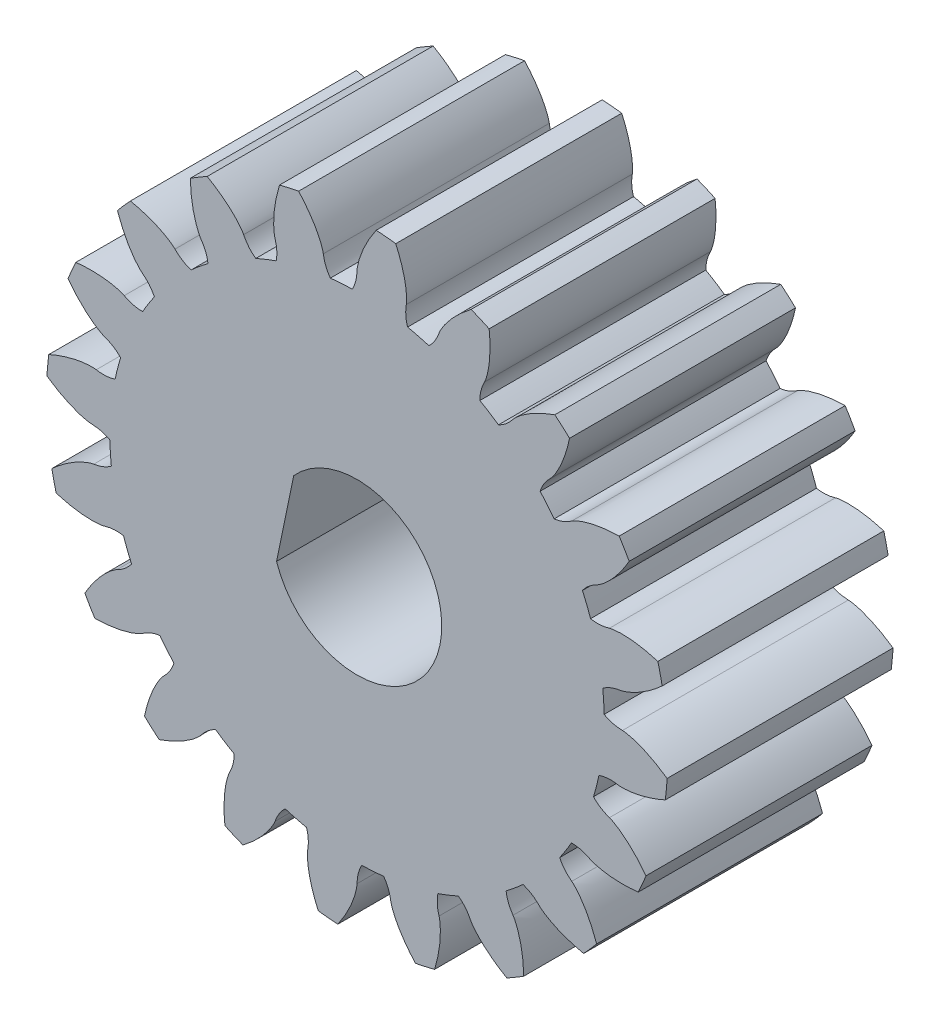
SolidWorks part; units mm, degrees
ref_plane "前视基准面" through (0, 0, 0) normal (0, 0, 1) x (1, 0, 0)
ref_plane "上视基准面" through (0, 0, 0) normal (0, 1, 0) x (1, 0, 0)
ref_plane "右视基准面" through (0, 0, 0) normal (1, 0, 0) x (0, 0, -1)
other "Configuration Table"
sketch "草图2" plane through (0, 0, 0) normal (0, 0, 1) x (1, 0, 0)
  line L0 (0, 0) -> (0.1489, 9.9989) construction
  line L1 (0, 0) -> (1.0263, 10.952) construction
  line L2 (0, 0) -> (2.6039, 10.1758) construction
  circle A0 centre (0, 0) radius 11
  circle A1 centre (0, 0) radius 8.75
  circle A2 centre (0, 0) radius 10
  spline S0 degree 4 poles (0, 9.3969) (0.0002, 9.4045) (0.0012, 9.4259) (0.0051, 9.4662) (0.0144, 9.5316) (0.0306, 9.6143) (0.0564, 9.7204) (0.0929, 9.844) (0.1395, 9.9782) (0.1971, 10.1222) (0.2605, 10.2637) (0.3292, 10.4028) (0.4026, 10.5394) (0.4972, 10.7023) (0.6185, 10.894) (0.7714, 11.1121) (0.9577, 11.3522) (1.1609, 11.5883) (1.3716, 11.8135) (1.5963, 12.032) (1.8221, 12.2371) (2.068, 12.4403) (2.3008, 12.6228) (2.5736, 12.8158) (2.7973, 12.9682) (3.1042, 13.1564) (3.289, 13.2637) (3.5092, 13.3847) (3.609, 13.436) (3.6704, 13.4676) knots 0 0 0 0 0 0.005377 0.015084 0.028532 0.04661 0.064855 0.092111 0.119476 0.146842 0.174209 0.201575 0.228941 0.256307 0.307035 0.361767 0.4165 0.471232 0.525964 0.580697 0.635429 0.690161 0.744894 0.799626 0.854358 0.909091 0.954545 1 1 1 1 1 construction
  spline S1 degree 4 poles (0, 9.3969) (0.0002, 9.4045) (0.0012, 9.4259) (0.0051, 9.4662) (0.0144, 9.5316) (0.0306, 9.6143) (0.0564, 9.7204) (0.0929, 9.844) (0.1395, 9.9782) (0.1971, 10.1222) (0.2605, 10.2637) (0.3292, 10.4028) (0.4026, 10.5394) (0.4971, 10.7022) (0.5769, 10.8283) (0.6386, 10.9201) (0.6797, 10.979) knots 0 0 0 0 0 0.005377 0.015084 0.028532 0.04661 0.064855 0.092111 0.119476 0.146842 0.174209 0.201575 0.228941 0.256307 0.306947 0.306947 0.306947 0.306947 0.306947
  spline S2 degree 3 poles (0, 9.3969) (-0.0051, 9.1654) (-0.0557, 8.9492) (-0.1677, 8.7484) knots 0 0 0 0 1 1 1 1
  spline S3 degree 4 poles (1.7457, 9.2333) (1.747, 9.2409) (1.75, 9.262) (1.7536, 9.3023) (1.7566, 9.3683) (1.7561, 9.4526) (1.7504, 9.5616) (1.7375, 9.6899) (1.7166, 9.8304) (1.6868, 9.9826) (1.6508, 10.1334) (1.6091, 10.2829) (1.5624, 10.4308) (1.4998, 10.6083) (1.4448, 10.747) (1.4012, 10.8486) (1.3718, 10.9141) knots 0 0 0 0 0 0.005377 0.015084 0.028532 0.04661 0.064855 0.092111 0.119476 0.146842 0.174209 0.201575 0.228941 0.256307 0.306947 0.306947 0.306947 0.306947 0.306947
  spline S4 degree 4 poles (2.9038, 8.937) (2.9063, 8.9442) (2.9139, 8.9642) (2.9301, 9.0013) (2.9591, 9.0606) (3.0001, 9.1343) (3.0574, 9.2272) (3.1304, 9.3335) (3.2161, 9.4467) (3.3154, 9.5658) (3.4194, 9.6809) (3.5278, 9.7919) (3.6398, 9.8992) (3.78, 10.0248) (3.8948, 10.12) (3.9819, 10.1883) (4.0391, 10.2316) knots 0 0 0 0 0 0.005377 0.015084 0.028532 0.04661 0.064855 0.092111 0.119476 0.146842 0.174209 0.201575 0.228941 0.256307 0.306947 0.306947 0.306947 0.306947 0.306947
  spline S5 degree 3 poles (1.7457, 9.2333) (1.7077, 9.0049) (1.7173, 8.783) (1.79, 8.5649) knots 0 0 0 0 1 1 1 1
  spline S6 degree 3 poles (2.9038, 8.937) (2.8274, 8.7184) (2.7125, 8.5284) (2.5439, 8.372) knots 0 0 0 0 1 1 1 1
  dimension "D1" = 20
  dimension "D2" = 22
  dimension "D3" = 17.5
  dimension "D5" = 4.5
  dimension "D6" = 13.5
sketch "草图4" plane through (0, 0, 0) normal (0, 0, 1) x (1, 0, 0)
  circle A0 centre (0, 0) radius 8.75 construction
  circle A1 centre (0, 0) radius 11 construction
  arc A2 (2.5439, 8.372) -> (1.79, 8.5649) centre (0, 0) ccw
  arc A3 (1.3718, 10.9141) -> (0.6797, 10.979) centre (0, 0) ccw
  arc A4 (4.6773, 9.956) -> (4.0391, 10.2316) centre (0, 0) ccw
  arc A5 (5.0065, 7.1762) -> (4.3492, 7.5926) centre (0, 0) ccw
  arc A6 (7.525, 8.0234) -> (7.0031, 8.4827) centre (0, 0) ccw
  arc A7 (6.979, 5.2779) -> (6.4825, 5.877) centre (0, 0) ccw
  arc A8 (9.6361, 5.3053) -> (9.2817, 5.9034) centre (0, 0) ccw
  arc A9 (8.2684, 2.8629) -> (7.9813, 3.5862) centre (0, 0) ccw
  arc A10 (10.8039, 2.068) -> (10.6517, 2.7463) centre (0, 0) ccw
  arc A11 (8.7484, 0.1677) -> (8.6989, 0.9443) centre (0, 0) ccw
  arc A12 (10.9141, -1.3718) -> (10.979, -0.6797) centre (0, 0) ccw
  arc A13 (8.372, -2.5439) -> (8.5649, -1.79) centre (0, 0) ccw
  arc A14 (9.956, -4.6773) -> (10.2316, -4.0391) centre (0, 0) ccw
  arc A15 (7.1762, -5.0065) -> (7.5926, -4.3492) centre (0, 0) ccw
  arc A16 (8.0234, -7.525) -> (8.4827, -7.0031) centre (0, 0) ccw
  arc A17 (5.2779, -6.979) -> (5.877, -6.4825) centre (0, 0) ccw
  arc A18 (5.3053, -9.6361) -> (5.9034, -9.2817) centre (0, 0) ccw
  arc A19 (2.8629, -8.2684) -> (3.5862, -7.9813) centre (0, 0) ccw
  arc A20 (2.068, -10.8039) -> (2.7463, -10.6517) centre (0, 0) ccw
  arc A21 (0.1677, -8.7484) -> (0.9443, -8.6989) centre (0, 0) ccw
  arc A22 (-1.3718, -10.9141) -> (-0.6797, -10.979) centre (0, 0) ccw
  arc A23 (-2.5439, -8.372) -> (-1.79, -8.5649) centre (0, 0) ccw
  arc A24 (-4.6773, -9.956) -> (-4.0391, -10.2316) centre (0, 0) ccw
  arc A25 (-5.0065, -7.1762) -> (-4.3492, -7.5926) centre (0, 0) ccw
  arc A26 (-7.525, -8.0234) -> (-7.0031, -8.4827) centre (0, 0) ccw
  arc A27 (-6.979, -5.2779) -> (-6.4825, -5.877) centre (0, 0) ccw
  arc A28 (-9.6361, -5.3053) -> (-9.2817, -5.9034) centre (0, 0) ccw
  arc A29 (-8.2684, -2.8629) -> (-7.9813, -3.5862) centre (0, 0) ccw
  arc A30 (-10.8039, -2.068) -> (-10.6517, -2.7463) centre (0, 0) ccw
  arc A31 (-8.7484, -0.1677) -> (-8.6989, -0.9443) centre (0, 0) ccw
  arc A32 (-10.9141, 1.3718) -> (-10.979, 0.6797) centre (0, 0) ccw
  arc A33 (-8.372, 2.5439) -> (-8.5649, 1.79) centre (0, 0) ccw
  arc A34 (-9.956, 4.6773) -> (-10.2316, 4.0391) centre (0, 0) ccw
  arc A35 (-7.1762, 5.0065) -> (-7.5926, 4.3492) centre (0, 0) ccw
  arc A36 (-8.0234, 7.525) -> (-8.4827, 7.0031) centre (0, 0) ccw
  arc A37 (-5.2779, 6.979) -> (-5.877, 6.4825) centre (0, 0) ccw
  arc A38 (-5.3053, 9.6361) -> (-5.9034, 9.2817) centre (0, 0) ccw
  arc A39 (-2.8629, 8.2684) -> (-3.5862, 7.9813) centre (0, 0) ccw
  arc A40 (-2.068, 10.8039) -> (-2.7463, 10.6517) centre (0, 0) ccw
  arc A41 (-0.1677, 8.7484) -> (-0.9443, 8.6989) centre (0, 0) ccw
  spline S0 degree 3 poles (2.9038, 8.937) (2.8274, 8.7184) (2.7125, 8.5284) (2.5439, 8.372) knots 0 0 0 0 1 1 1 1
  spline S2 degree 3 poles (-1934.3445, 507) (1990.5579, -354.5504) (-1998.9615, 305.4364) (1982.4508, -268.4283) knots -53.013811 -53.013811 -53.013811 -53.013811 47.32506 47.32506 47.32506 47.32506 only from (1.7457, 9.2333) to (1.79, 8.5649) construction
  spline S3 degree 3 poles (1994.8605, 138.8139) (-2021.7734, 21.4251) (2020.9063, -71.2453) (-1997.8078, 104.5418) knots -53.013811 -53.013811 -53.013811 -53.013811 47.32506 47.32506 47.32506 47.32506 only from (0, 9.3969) to (-0.1677, 8.7484) construction
  spline S4 degree 4 poles (-1966.019, 366.2112) (-26.0757, 12.0563) (1.0255, 7.8303) (1.7205, 8.5676) (1.7566, 9.3683) (1.7561, 9.4526) (1.7504, 9.5616) (1.7375, 9.6899) (1.7166, 9.8304) (1.6868, 9.9826) (1.6508, 10.1334) (1.6091, 10.2829) (1.5624, 10.4308) (0.1488, 14.4374) (-5.4103, 16.6364) (-16.4638, 28.6234) (1468.9037, -1347.863) knots -0.51893 -0.51893 -0.51893 -0.51893 -0.51893 0.005377 0.015084 0.028532 0.04661 0.064855 0.092111 0.119476 0.146842 0.174209 0.201575 0.228941 0.256307 3.170222 3.170222 3.170222 3.170222 3.170222 only from (1.7457, 9.2333) to (1.3718, 10.9141) construction
  spline S5 degree 4 poles (1999.828, -5.4085) (27.8615, 7.0021) (0.4471, 7.8845) (-0.0989, 8.7381) (0.0144, 9.5316) (0.0306, 9.6143) (0.0564, 9.7204) (0.0929, 9.844) (0.1395, 9.9782) (0.1971, 10.1222) (0.2605, 10.2637) (0.3292, 10.4028) (0.4026, 10.5394) (2.536, 14.2137) (8.4068, 15.3416) (21.4948, 25.0665) (-1693.7368, -1051.5077) knots -0.51893 -0.51893 -0.51893 -0.51893 -0.51893 0.005377 0.015084 0.028532 0.04661 0.064855 0.092111 0.119476 0.146842 0.174209 0.201575 0.228941 0.256307 3.170222 3.170222 3.170222 3.170222 3.170222 only from (0, 9.3969) to (0.6797, 10.979) construction
  spline S6 degree 4 poles (2.9038, 8.937) (2.9063, 8.9442) (2.9139, 8.9642) (2.9301, 9.0013) (2.9591, 9.0606) (3.0001, 9.1343) (3.0574, 9.2272) (3.1304, 9.3335) (3.2161, 9.4467) (3.3154, 9.5658) (3.4194, 9.6809) (3.5278, 9.7919) (3.6398, 9.8992) (3.78, 10.0248) (3.8948, 10.12) (3.9819, 10.1883) (4.0391, 10.2316) knots 0 0 0 0 0 0.005377 0.015084 0.028532 0.04661 0.064855 0.092111 0.119476 0.146842 0.174209 0.201575 0.228941 0.256307 0.306947 0.306947 0.306947 0.306947 0.306947
  spline S7 degree 4 poles (4.5136, 8.242) (4.5171, 8.2487) (4.5265, 8.2679) (4.5423, 8.3051) (4.5656, 8.367) (4.5911, 8.4473) (4.6195, 8.5527) (4.6468, 8.6787) (4.6704, 8.8188) (4.689, 8.9727) (4.7014, 9.1273) (4.708, 9.2824) (4.7092, 9.4374) (4.7045, 9.6256) (4.6951, 9.7745) (4.685, 9.8847) (4.6773, 9.956) knots 0 0 0 0 0 0.005377 0.015084 0.028532 0.04661 0.064855 0.092111 0.119476 0.146842 0.174209 0.201575 0.228941 0.256307 0.306947 0.306947 0.306947 0.306947 0.306947
  spline S8 degree 3 poles (1.7457, 9.2333) (1.7077, 9.0049) (1.7173, 8.783) (1.79, 8.5649) knots 0 0 0 0 1 1 1 1
  spline S9 degree 3 poles (0, 9.3969) (-0.0051, 9.1654) (-0.0557, 8.9492) (-0.1677, 8.7484) knots 0 0 0 0 1 1 1 1
  spline S10 degree 4 poles (1.7457, 9.2333) (1.747, 9.2409) (1.75, 9.262) (1.7536, 9.3023) (1.7566, 9.3683) (1.7561, 9.4526) (1.7504, 9.5616) (1.7375, 9.6899) (1.7166, 9.8304) (1.6868, 9.9826) (1.6508, 10.1334) (1.6091, 10.2829) (1.5624, 10.4308) (1.4998, 10.6083) (1.4448, 10.747) (1.4012, 10.8486) (1.3718, 10.9141) knots 0 0 0 0 0 0.005377 0.015084 0.028532 0.04661 0.064855 0.092111 0.119476 0.146842 0.174209 0.201575 0.228941 0.256307 0.306947 0.306947 0.306947 0.306947 0.306947
  spline S11 degree 4 poles (0, 9.3969) (0.0002, 9.4045) (0.0012, 9.4259) (0.0051, 9.4662) (0.0144, 9.5316) (0.0306, 9.6143) (0.0564, 9.7204) (0.0929, 9.844) (0.1395, 9.9782) (0.1971, 10.1222) (0.2605, 10.2637) (0.3292, 10.4028) (0.4026, 10.5394) (0.4971, 10.7022) (0.5769, 10.8283) (0.6386, 10.9201) (0.6797, 10.979) knots 0 0 0 0 0 0.005377 0.015084 0.028532 0.04661 0.064855 0.092111 0.119476 0.146842 0.174209 0.201575 0.228941 0.256307 0.306947 0.306947 0.306947 0.306947 0.306947
  spline S12 degree 3 poles (4.5136, 8.242) (4.4068, 8.0365) (4.3473, 7.8225) (4.3492, 7.5926) knots 0 0 0 0 1 1 1 1
  spline S13 degree 3 poles (5.5234, 7.6023) (5.3832, 7.418) (5.2151, 7.2727) (5.0065, 7.1762) knots 0 0 0 0 1 1 1 1
  spline S14 degree 4 poles (5.5234, 7.6023) (5.528, 7.6083) (5.5413, 7.625) (5.5682, 7.6553) (5.6142, 7.7027) (5.6759, 7.7601) (5.7591, 7.8308) (5.8614, 7.9094) (5.9779, 7.9905) (6.1091, 8.0731) (6.2436, 8.1504) (6.381, 8.2226) (6.5207, 8.2899) (6.6928, 8.3661) (6.8314, 8.4212) (6.9353, 8.4592) (7.0031, 8.4827) knots 0 0 0 0 0 0.005377 0.015084 0.028532 0.04661 0.064855 0.092111 0.119476 0.146842 0.174209 0.201575 0.228941 0.256307 0.306947 0.306947 0.306947 0.306947 0.306947
  spline S15 degree 4 poles (6.8396, 6.4438) (6.845, 6.4492) (6.8599, 6.4645) (6.8865, 6.495) (6.9276, 6.5466) (6.9768, 6.6151) (7.0363, 6.7066) (7.1013, 6.818) (7.167, 6.944) (7.2323, 7.0846) (7.2918, 7.2278) (7.3459, 7.3732) (7.395, 7.5203) (7.4487, 7.7007) (7.4858, 7.8452) (7.5103, 7.9531) (7.525, 8.0234) knots 0 0 0 0 0 0.005377 0.015084 0.028532 0.04661 0.064855 0.092111 0.119476 0.146842 0.174209 0.201575 0.228941 0.256307 0.306947 0.306947 0.306947 0.306947 0.306947
  spline S16 degree 3 poles (6.8396, 6.4438) (6.6746, 6.2813) (6.5518, 6.0962) (6.4825, 5.877) knots 0 0 0 0 1 1 1 1
  spline S17 degree 3 poles (7.6023, 5.5234) (7.412, 5.3914) (7.2073, 5.3052) (6.979, 5.2779) knots 0 0 0 0 1 1 1 1
  spline S18 degree 4 poles (7.6023, 5.5234) (7.6085, 5.5277) (7.6264, 5.5395) (7.6613, 5.5599) (7.7197, 5.5908) (7.7961, 5.6264) (7.8971, 5.6679) (8.0186, 5.711) (8.1546, 5.7522) (8.3048, 5.7902) (8.4566, 5.8221) (8.6096, 5.8483) (8.7632, 5.8692) (8.9505, 5.8884) (9.0994, 5.898) (9.2099, 5.902) (9.2817, 5.9034) knots 0 0 0 0 0 0.005377 0.015084 0.028532 0.04661 0.064855 0.092111 0.119476 0.146842 0.174209 0.201575 0.228941 0.256307 0.306947 0.306947 0.306947 0.306947 0.306947
  spline S19 degree 4 poles (8.4961, 4.0149) (8.5029, 4.0183) (8.5218, 4.0283) (8.5565, 4.0491) (8.6116, 4.0855) (8.6795, 4.1354) (8.7644, 4.2041) (8.8606, 4.2899) (8.962, 4.3894) (9.0676, 4.5029) (9.1684, 4.6207) (9.2649, 4.7423) (9.357, 4.8671) (9.4638, 5.0221) (9.5437, 5.148) (9.6003, 5.2431) (9.6361, 5.3053) knots 0 0 0 0 0 0.005377 0.015084 0.028532 0.04661 0.064855 0.092111 0.119476 0.146842 0.174209 0.201575 0.228941 0.256307 0.306947 0.306947 0.306947 0.306947 0.306947
  spline S20 degree 3 poles (8.4961, 4.0149) (8.2889, 3.9114) (8.115, 3.7732) (7.9813, 3.5862) knots 0 0 0 0 1 1 1 1
  spline S21 degree 3 poles (8.937, 2.9038) (8.7153, 2.8371) (8.494, 2.8184) (8.2684, 2.8629) knots 0 0 0 0 1 1 1 1
  spline S22 degree 4 poles (8.937, 2.9038) (8.9443, 2.906) (8.9649, 2.9117) (9.0044, 2.9204) (9.0695, 2.9317) (9.1532, 2.9419) (9.2621, 2.9502) (9.3909, 2.9536) (9.533, 2.9507) (9.6876, 2.9405) (9.8419, 2.9239) (9.9954, 2.9015) (10.148, 2.8739) (10.332, 2.8344) (10.4766, 2.7974) (10.583, 2.7671) (10.6517, 2.7463) knots 0 0 0 0 0 0.005377 0.015084 0.028532 0.04661 0.064855 0.092111 0.119476 0.146842 0.174209 0.201575 0.228941 0.256307 0.306947 0.306947 0.306947 0.306947 0.306947
  spline S23 degree 4 poles (9.3209, 1.193) (9.3284, 1.1941) (9.3495, 1.1978) (9.3889, 1.2068) (9.4526, 1.2244) (9.5326, 1.2509) (9.6346, 1.2899) (9.7526, 1.3419) (9.8798, 1.4052) (10.0152, 1.4805) (10.1476, 1.5614) (10.2769, 1.6472) (10.403, 1.7374) (10.5525, 1.8518) (10.6674, 1.9469) (10.7507, 2.0198) (10.8039, 2.068) knots 0 0 0 0 0 0.005377 0.015084 0.028532 0.04661 0.064855 0.092111 0.119476 0.146842 0.174209 0.201575 0.228941 0.256307 0.306947 0.306947 0.306947 0.306947 0.306947
  spline S24 degree 3 poles (9.3209, 1.193) (9.0919, 1.1585) (8.8838, 1.0809) (8.6989, 0.9443) knots 0 0 0 0 1 1 1 1
  spline S25 degree 3 poles (9.3969, 0) (9.1654, 0.0051) (8.9492, 0.0557) (8.7484, 0.1677) knots 0 0 0 0 1 1 1 1
  spline S26 degree 4 poles (9.3969, 0) (9.4045, -0.0002) (9.4259, -0.0012) (9.4662, -0.0051) (9.5316, -0.0144) (9.6143, -0.0306) (9.7204, -0.0564) (9.844, -0.0929) (9.9782, -0.1395) (10.1222, -0.1971) (10.2637, -0.2605) (10.4028, -0.3292) (10.5394, -0.4026) (10.7022, -0.4971) (10.8283, -0.5769) (10.9201, -0.6386) (10.979, -0.6797) knots 0 0 0 0 0 0.005377 0.015084 0.028532 0.04661 0.064855 0.092111 0.119476 0.146842 0.174209 0.201575 0.228941 0.256307 0.306947 0.306947 0.306947 0.306947 0.306947
  spline S27 degree 4 poles (9.2333, -1.7457) (9.2409, -1.747) (9.262, -1.75) (9.3023, -1.7536) (9.3683, -1.7566) (9.4526, -1.7561) (9.5616, -1.7504) (9.6899, -1.7375) (9.8304, -1.7166) (9.9826, -1.6868) (10.1334, -1.6508) (10.2829, -1.6091) (10.4308, -1.5624) (10.6083, -1.4998) (10.747, -1.4448) (10.8486, -1.4012) (10.9141, -1.3718) knots 0 0 0 0 0 0.005377 0.015084 0.028532 0.04661 0.064855 0.092111 0.119476 0.146842 0.174209 0.201575 0.228941 0.256307 0.306947 0.306947 0.306947 0.306947 0.306947
  spline S28 degree 3 poles (9.2333, -1.7457) (9.0049, -1.7077) (8.783, -1.7173) (8.5649, -1.79) knots 0 0 0 0 1 1 1 1
  spline S29 degree 3 poles (8.937, -2.9038) (8.7184, -2.8274) (8.5284, -2.7125) (8.372, -2.5439) knots 0 0 0 0 1 1 1 1
  spline S30 degree 4 poles (8.937, -2.9038) (8.9442, -2.9063) (8.9642, -2.9139) (9.0013, -2.9301) (9.0606, -2.9591) (9.1343, -3.0001) (9.2272, -3.0574) (9.3335, -3.1304) (9.4467, -3.2161) (9.5658, -3.3154) (9.6809, -3.4194) (9.7919, -3.5278) (9.8992, -3.6398) (10.0248, -3.78) (10.12, -3.8948) (10.1883, -3.9819) (10.2316, -4.0391) knots 0 0 0 0 0 0.005377 0.015084 0.028532 0.04661 0.064855 0.092111 0.119476 0.146842 0.174209 0.201575 0.228941 0.256307 0.306947 0.306947 0.306947 0.306947 0.306947
  spline S31 degree 4 poles (8.242, -4.5136) (8.2487, -4.5171) (8.2679, -4.5265) (8.3051, -4.5423) (8.367, -4.5656) (8.4473, -4.5911) (8.5527, -4.6195) (8.6787, -4.6468) (8.8188, -4.6704) (8.9727, -4.689) (9.1273, -4.7014) (9.2824, -4.708) (9.4374, -4.7092) (9.6256, -4.7045) (9.7745, -4.6951) (9.8847, -4.685) (9.956, -4.6773) knots 0 0 0 0 0 0.005377 0.015084 0.028532 0.04661 0.064855 0.092111 0.119476 0.146842 0.174209 0.201575 0.228941 0.256307 0.306947 0.306947 0.306947 0.306947 0.306947
  spline S32 degree 3 poles (8.242, -4.5136) (8.0365, -4.4068) (7.8225, -4.3473) (7.5926, -4.3492) knots 0 0 0 0 1 1 1 1
  spline S33 degree 3 poles (7.6023, -5.5234) (7.418, -5.3832) (7.2727, -5.2151) (7.1762, -5.0065) knots 0 0 0 0 1 1 1 1
  spline S34 degree 4 poles (7.6023, -5.5234) (7.6083, -5.528) (7.625, -5.5413) (7.6553, -5.5682) (7.7027, -5.6142) (7.7601, -5.6759) (7.8308, -5.7591) (7.9094, -5.8614) (7.9905, -5.9779) (8.0731, -6.1091) (8.1504, -6.2436) (8.2226, -6.381) (8.2899, -6.5207) (8.3661, -6.6928) (8.4212, -6.8314) (8.4592, -6.9353) (8.4827, -7.0031) knots 0 0 0 0 0 0.005377 0.015084 0.028532 0.04661 0.064855 0.092111 0.119476 0.146842 0.174209 0.201575 0.228941 0.256307 0.306947 0.306947 0.306947 0.306947 0.306947
  spline S35 degree 4 poles (6.4438, -6.8396) (6.4492, -6.845) (6.4645, -6.8599) (6.495, -6.8865) (6.5466, -6.9276) (6.6151, -6.9768) (6.7066, -7.0363) (6.818, -7.1013) (6.944, -7.167) (7.0846, -7.2323) (7.2278, -7.2918) (7.3732, -7.3459) (7.5203, -7.395) (7.7007, -7.4487) (7.8452, -7.4858) (7.9531, -7.5103) (8.0234, -7.525) knots 0 0 0 0 0 0.005377 0.015084 0.028532 0.04661 0.064855 0.092111 0.119476 0.146842 0.174209 0.201575 0.228941 0.256307 0.306947 0.306947 0.306947 0.306947 0.306947
  spline S36 degree 3 poles (6.4438, -6.8396) (6.2813, -6.6746) (6.0962, -6.5518) (5.877, -6.4825) knots 0 0 0 0 1 1 1 1
  spline S37 degree 3 poles (5.5234, -7.6023) (5.3914, -7.412) (5.3052, -7.2073) (5.2779, -6.979) knots 0 0 0 0 1 1 1 1
  spline S38 degree 4 poles (5.5234, -7.6023) (5.5277, -7.6085) (5.5395, -7.6264) (5.5599, -7.6613) (5.5908, -7.7197) (5.6264, -7.7961) (5.6679, -7.8971) (5.711, -8.0186) (5.7522, -8.1546) (5.7902, -8.3048) (5.8221, -8.4566) (5.8483, -8.6096) (5.8692, -8.7632) (5.8884, -8.9505) (5.898, -9.0994) (5.902, -9.2099) (5.9034, -9.2817) knots 0 0 0 0 0 0.005377 0.015084 0.028532 0.04661 0.064855 0.092111 0.119476 0.146842 0.174209 0.201575 0.228941 0.256307 0.306947 0.306947 0.306947 0.306947 0.306947
  spline S39 degree 4 poles (4.0149, -8.4961) (4.0183, -8.5029) (4.0283, -8.5218) (4.0491, -8.5565) (4.0855, -8.6116) (4.1354, -8.6795) (4.2041, -8.7644) (4.2899, -8.8606) (4.3894, -8.962) (4.5029, -9.0676) (4.6207, -9.1684) (4.7423, -9.2649) (4.8671, -9.357) (5.0221, -9.4638) (5.148, -9.5437) (5.2431, -9.6003) (5.3053, -9.6361) knots 0 0 0 0 0 0.005377 0.015084 0.028532 0.04661 0.064855 0.092111 0.119476 0.146842 0.174209 0.201575 0.228941 0.256307 0.306947 0.306947 0.306947 0.306947 0.306947
  spline S40 degree 3 poles (4.0149, -8.4961) (3.9114, -8.2889) (3.7732, -8.115) (3.5862, -7.9813) knots 0 0 0 0 1 1 1 1
  spline S41 degree 3 poles (2.9038, -8.937) (2.8371, -8.7153) (2.8184, -8.494) (2.8629, -8.2684) knots 0 0 0 0 1 1 1 1
  spline S42 degree 4 poles (2.9038, -8.937) (2.906, -8.9443) (2.9117, -8.9649) (2.9204, -9.0044) (2.9317, -9.0695) (2.9419, -9.1532) (2.9502, -9.2621) (2.9536, -9.3909) (2.9507, -9.533) (2.9405, -9.6876) (2.9239, -9.8419) (2.9015, -9.9954) (2.8739, -10.148) (2.8344, -10.332) (2.7974, -10.4766) (2.7671, -10.583) (2.7463, -10.6517) knots 0 0 0 0 0 0.005377 0.015084 0.028532 0.04661 0.064855 0.092111 0.119476 0.146842 0.174209 0.201575 0.228941 0.256307 0.306947 0.306947 0.306947 0.306947 0.306947
  spline S43 degree 4 poles (1.193, -9.3209) (1.1941, -9.3284) (1.1978, -9.3495) (1.2068, -9.3889) (1.2244, -9.4526) (1.2509, -9.5326) (1.2899, -9.6346) (1.3419, -9.7526) (1.4052, -9.8798) (1.4805, -10.0152) (1.5614, -10.1476) (1.6472, -10.2769) (1.7374, -10.403) (1.8518, -10.5525) (1.9469, -10.6674) (2.0198, -10.7507) (2.068, -10.8039) knots 0 0 0 0 0 0.005377 0.015084 0.028532 0.04661 0.064855 0.092111 0.119476 0.146842 0.174209 0.201575 0.228941 0.256307 0.306947 0.306947 0.306947 0.306947 0.306947
  spline S44 degree 3 poles (1.193, -9.3209) (1.1585, -9.0919) (1.0809, -8.8838) (0.9443, -8.6989) knots 0 0 0 0 1 1 1 1
  spline S45 degree 3 poles (0, -9.3969) (0.0051, -9.1654) (0.0557, -8.9492) (0.1677, -8.7484) knots 0 0 0 0 1 1 1 1
  spline S46 degree 4 poles (0, -9.3969) (-0.0002, -9.4045) (-0.0012, -9.4259) (-0.0051, -9.4662) (-0.0144, -9.5316) (-0.0306, -9.6143) (-0.0564, -9.7204) (-0.0929, -9.844) (-0.1395, -9.9782) (-0.1971, -10.1222) (-0.2605, -10.2637) (-0.3292, -10.4028) (-0.4026, -10.5394) (-0.4971, -10.7022) (-0.5769, -10.8283) (-0.6386, -10.9201) (-0.6797, -10.979) knots 0 0 0 0 0 0.005377 0.015084 0.028532 0.04661 0.064855 0.092111 0.119476 0.146842 0.174209 0.201575 0.228941 0.256307 0.306947 0.306947 0.306947 0.306947 0.306947
  spline S47 degree 4 poles (-1.7457, -9.2333) (-1.747, -9.2409) (-1.75, -9.262) (-1.7536, -9.3023) (-1.7566, -9.3683) (-1.7561, -9.4526) (-1.7504, -9.5616) (-1.7375, -9.6899) (-1.7166, -9.8304) (-1.6868, -9.9826) (-1.6508, -10.1334) (-1.6091, -10.2829) (-1.5624, -10.4308) (-1.4998, -10.6083) (-1.4448, -10.747) (-1.4012, -10.8486) (-1.3718, -10.9141) knots 0 0 0 0 0 0.005377 0.015084 0.028532 0.04661 0.064855 0.092111 0.119476 0.146842 0.174209 0.201575 0.228941 0.256307 0.306947 0.306947 0.306947 0.306947 0.306947
  spline S48 degree 3 poles (-1.7457, -9.2333) (-1.7077, -9.0049) (-1.7173, -8.783) (-1.79, -8.5649) knots 0 0 0 0 1 1 1 1
  spline S49 degree 3 poles (-2.9038, -8.937) (-2.8274, -8.7184) (-2.7125, -8.5284) (-2.5439, -8.372) knots 0 0 0 0 1 1 1 1
  spline S50 degree 4 poles (-2.9038, -8.937) (-2.9063, -8.9442) (-2.9139, -8.9642) (-2.9301, -9.0013) (-2.9591, -9.0606) (-3.0001, -9.1343) (-3.0574, -9.2272) (-3.1304, -9.3335) (-3.2161, -9.4467) (-3.3154, -9.5658) (-3.4194, -9.6809) (-3.5278, -9.7919) (-3.6398, -9.8992) (-3.78, -10.0248) (-3.8948, -10.12) (-3.9819, -10.1883) (-4.0391, -10.2316) knots 0 0 0 0 0 0.005377 0.015084 0.028532 0.04661 0.064855 0.092111 0.119476 0.146842 0.174209 0.201575 0.228941 0.256307 0.306947 0.306947 0.306947 0.306947 0.306947
  spline S51 degree 4 poles (-4.5136, -8.242) (-4.5171, -8.2487) (-4.5265, -8.2679) (-4.5423, -8.3051) (-4.5656, -8.367) (-4.5911, -8.4473) (-4.6195, -8.5527) (-4.6468, -8.6787) (-4.6704, -8.8188) (-4.689, -8.9727) (-4.7014, -9.1273) (-4.708, -9.2824) (-4.7092, -9.4374) (-4.7045, -9.6256) (-4.6951, -9.7745) (-4.685, -9.8847) (-4.6773, -9.956) knots 0 0 0 0 0 0.005377 0.015084 0.028532 0.04661 0.064855 0.092111 0.119476 0.146842 0.174209 0.201575 0.228941 0.256307 0.306947 0.306947 0.306947 0.306947 0.306947
  spline S52 degree 3 poles (-4.5136, -8.242) (-4.4068, -8.0365) (-4.3473, -7.8225) (-4.3492, -7.5926) knots 0 0 0 0 1 1 1 1
  spline S53 degree 3 poles (-5.5234, -7.6023) (-5.3832, -7.418) (-5.2151, -7.2727) (-5.0065, -7.1762) knots 0 0 0 0 1 1 1 1
  spline S54 degree 4 poles (-5.5234, -7.6023) (-5.528, -7.6083) (-5.5413, -7.625) (-5.5682, -7.6553) (-5.6142, -7.7027) (-5.6759, -7.7601) (-5.7591, -7.8308) (-5.8614, -7.9094) (-5.9779, -7.9905) (-6.1091, -8.0731) (-6.2436, -8.1504) (-6.381, -8.2226) (-6.5207, -8.2899) (-6.6928, -8.3661) (-6.8314, -8.4212) (-6.9353, -8.4592) (-7.0031, -8.4827) knots 0 0 0 0 0 0.005377 0.015084 0.028532 0.04661 0.064855 0.092111 0.119476 0.146842 0.174209 0.201575 0.228941 0.256307 0.306947 0.306947 0.306947 0.306947 0.306947
  spline S55 degree 4 poles (-6.8396, -6.4438) (-6.845, -6.4492) (-6.8599, -6.4645) (-6.8865, -6.495) (-6.9276, -6.5466) (-6.9768, -6.6151) (-7.0363, -6.7066) (-7.1013, -6.818) (-7.167, -6.944) (-7.2323, -7.0846) (-7.2918, -7.2278) (-7.3459, -7.3732) (-7.395, -7.5203) (-7.4487, -7.7007) (-7.4858, -7.8452) (-7.5103, -7.9531) (-7.525, -8.0234) knots 0 0 0 0 0 0.005377 0.015084 0.028532 0.04661 0.064855 0.092111 0.119476 0.146842 0.174209 0.201575 0.228941 0.256307 0.306947 0.306947 0.306947 0.306947 0.306947
  spline S56 degree 3 poles (-6.8396, -6.4438) (-6.6746, -6.2813) (-6.5518, -6.0962) (-6.4825, -5.877) knots 0 0 0 0 1 1 1 1
  spline S57 degree 3 poles (-7.6023, -5.5234) (-7.412, -5.3914) (-7.2073, -5.3052) (-6.979, -5.2779) knots 0 0 0 0 1 1 1 1
  spline S58 degree 4 poles (-7.6023, -5.5234) (-7.6085, -5.5277) (-7.6264, -5.5395) (-7.6613, -5.5599) (-7.7197, -5.5908) (-7.7961, -5.6264) (-7.8971, -5.6679) (-8.0186, -5.711) (-8.1546, -5.7522) (-8.3048, -5.7902) (-8.4566, -5.8221) (-8.6096, -5.8483) (-8.7632, -5.8692) (-8.9505, -5.8884) (-9.0994, -5.898) (-9.2099, -5.902) (-9.2817, -5.9034) knots 0 0 0 0 0 0.005377 0.015084 0.028532 0.04661 0.064855 0.092111 0.119476 0.146842 0.174209 0.201575 0.228941 0.256307 0.306947 0.306947 0.306947 0.306947 0.306947
  spline S59 degree 4 poles (-8.4961, -4.0149) (-8.5029, -4.0183) (-8.5218, -4.0283) (-8.5565, -4.0491) (-8.6116, -4.0855) (-8.6795, -4.1354) (-8.7644, -4.2041) (-8.8606, -4.2899) (-8.962, -4.3894) (-9.0676, -4.5029) (-9.1684, -4.6207) (-9.2649, -4.7423) (-9.357, -4.8671) (-9.4638, -5.0221) (-9.5437, -5.148) (-9.6003, -5.2431) (-9.6361, -5.3053) knots 0 0 0 0 0 0.005377 0.015084 0.028532 0.04661 0.064855 0.092111 0.119476 0.146842 0.174209 0.201575 0.228941 0.256307 0.306947 0.306947 0.306947 0.306947 0.306947
  spline S60 degree 3 poles (-8.4961, -4.0149) (-8.2889, -3.9114) (-8.115, -3.7732) (-7.9813, -3.5862) knots 0 0 0 0 1 1 1 1
  spline S61 degree 3 poles (-8.937, -2.9038) (-8.7153, -2.8371) (-8.494, -2.8184) (-8.2684, -2.8629) knots 0 0 0 0 1 1 1 1
  spline S62 degree 4 poles (-8.937, -2.9038) (-8.9443, -2.906) (-8.9649, -2.9117) (-9.0044, -2.9204) (-9.0695, -2.9317) (-9.1532, -2.9419) (-9.2621, -2.9502) (-9.3909, -2.9536) (-9.533, -2.9507) (-9.6876, -2.9405) (-9.8419, -2.9239) (-9.9954, -2.9015) (-10.148, -2.8739) (-10.332, -2.8344) (-10.4766, -2.7974) (-10.583, -2.7671) (-10.6517, -2.7463) knots 0 0 0 0 0 0.005377 0.015084 0.028532 0.04661 0.064855 0.092111 0.119476 0.146842 0.174209 0.201575 0.228941 0.256307 0.306947 0.306947 0.306947 0.306947 0.306947
  spline S63 degree 4 poles (-9.3209, -1.193) (-9.3284, -1.1941) (-9.3495, -1.1978) (-9.3889, -1.2068) (-9.4526, -1.2244) (-9.5326, -1.2509) (-9.6346, -1.2899) (-9.7526, -1.3419) (-9.8798, -1.4052) (-10.0152, -1.4805) (-10.1476, -1.5614) (-10.2769, -1.6472) (-10.403, -1.7374) (-10.5525, -1.8518) (-10.6674, -1.9469) (-10.7507, -2.0198) (-10.8039, -2.068) knots 0 0 0 0 0 0.005377 0.015084 0.028532 0.04661 0.064855 0.092111 0.119476 0.146842 0.174209 0.201575 0.228941 0.256307 0.306947 0.306947 0.306947 0.306947 0.306947
  spline S64 degree 3 poles (-9.3209, -1.193) (-9.0919, -1.1585) (-8.8838, -1.0809) (-8.6989, -0.9443) knots 0 0 0 0 1 1 1 1
  spline S65 degree 3 poles (-9.3969, 0) (-9.1654, -0.0051) (-8.9492, -0.0557) (-8.7484, -0.1677) knots 0 0 0 0 1 1 1 1
  spline S66 degree 4 poles (-9.3969, 0) (-9.4045, 0.0002) (-9.4259, 0.0012) (-9.4662, 0.0051) (-9.5316, 0.0144) (-9.6143, 0.0306) (-9.7204, 0.0564) (-9.844, 0.0929) (-9.9782, 0.1395) (-10.1222, 0.1971) (-10.2637, 0.2605) (-10.4028, 0.3292) (-10.5394, 0.4026) (-10.7022, 0.4971) (-10.8283, 0.5769) (-10.9201, 0.6386) (-10.979, 0.6797) knots 0 0 0 0 0 0.005377 0.015084 0.028532 0.04661 0.064855 0.092111 0.119476 0.146842 0.174209 0.201575 0.228941 0.256307 0.306947 0.306947 0.306947 0.306947 0.306947
  spline S67 degree 4 poles (-9.2333, 1.7457) (-9.2409, 1.747) (-9.262, 1.75) (-9.3023, 1.7536) (-9.3683, 1.7566) (-9.4526, 1.7561) (-9.5616, 1.7504) (-9.6899, 1.7375) (-9.8304, 1.7166) (-9.9826, 1.6868) (-10.1334, 1.6508) (-10.2829, 1.6091) (-10.4308, 1.5624) (-10.6083, 1.4998) (-10.747, 1.4448) (-10.8486, 1.4012) (-10.9141, 1.3718) knots 0 0 0 0 0 0.005377 0.015084 0.028532 0.04661 0.064855 0.092111 0.119476 0.146842 0.174209 0.201575 0.228941 0.256307 0.306947 0.306947 0.306947 0.306947 0.306947
  spline S68 degree 3 poles (-9.2333, 1.7457) (-9.0049, 1.7077) (-8.783, 1.7173) (-8.5649, 1.79) knots 0 0 0 0 1 1 1 1
  spline S69 degree 3 poles (-8.937, 2.9038) (-8.7184, 2.8274) (-8.5284, 2.7125) (-8.372, 2.5439) knots 0 0 0 0 1 1 1 1
  spline S70 degree 4 poles (-8.937, 2.9038) (-8.9442, 2.9063) (-8.9642, 2.9139) (-9.0013, 2.9301) (-9.0606, 2.9591) (-9.1343, 3.0001) (-9.2272, 3.0574) (-9.3335, 3.1304) (-9.4467, 3.2161) (-9.5658, 3.3154) (-9.6809, 3.4194) (-9.7919, 3.5278) (-9.8992, 3.6398) (-10.0248, 3.78) (-10.12, 3.8948) (-10.1883, 3.9819) (-10.2316, 4.0391) knots 0 0 0 0 0 0.005377 0.015084 0.028532 0.04661 0.064855 0.092111 0.119476 0.146842 0.174209 0.201575 0.228941 0.256307 0.306947 0.306947 0.306947 0.306947 0.306947
  spline S71 degree 4 poles (-8.242, 4.5136) (-8.2487, 4.5171) (-8.2679, 4.5265) (-8.3051, 4.5423) (-8.367, 4.5656) (-8.4473, 4.5911) (-8.5527, 4.6195) (-8.6787, 4.6468) (-8.8188, 4.6704) (-8.9727, 4.689) (-9.1273, 4.7014) (-9.2824, 4.708) (-9.4374, 4.7092) (-9.6256, 4.7045) (-9.7745, 4.6951) (-9.8847, 4.685) (-9.956, 4.6773) knots 0 0 0 0 0 0.005377 0.015084 0.028532 0.04661 0.064855 0.092111 0.119476 0.146842 0.174209 0.201575 0.228941 0.256307 0.306947 0.306947 0.306947 0.306947 0.306947
  spline S72 degree 3 poles (-8.242, 4.5136) (-8.0365, 4.4068) (-7.8225, 4.3473) (-7.5926, 4.3492) knots 0 0 0 0 1 1 1 1
  spline S73 degree 3 poles (-7.6023, 5.5234) (-7.418, 5.3832) (-7.2727, 5.2151) (-7.1762, 5.0065) knots 0 0 0 0 1 1 1 1
  spline S74 degree 4 poles (-7.6023, 5.5234) (-7.6083, 5.528) (-7.625, 5.5413) (-7.6553, 5.5682) (-7.7027, 5.6142) (-7.7601, 5.6759) (-7.8308, 5.7591) (-7.9094, 5.8614) (-7.9905, 5.9779) (-8.0731, 6.1091) (-8.1504, 6.2436) (-8.2226, 6.381) (-8.2899, 6.5207) (-8.3661, 6.6928) (-8.4212, 6.8314) (-8.4592, 6.9353) (-8.4827, 7.0031) knots 0 0 0 0 0 0.005377 0.015084 0.028532 0.04661 0.064855 0.092111 0.119476 0.146842 0.174209 0.201575 0.228941 0.256307 0.306947 0.306947 0.306947 0.306947 0.306947
  spline S75 degree 4 poles (-6.4438, 6.8396) (-6.4492, 6.845) (-6.4645, 6.8599) (-6.495, 6.8865) (-6.5466, 6.9276) (-6.6151, 6.9768) (-6.7066, 7.0363) (-6.818, 7.1013) (-6.944, 7.167) (-7.0846, 7.2323) (-7.2278, 7.2918) (-7.3732, 7.3459) (-7.5203, 7.395) (-7.7007, 7.4487) (-7.8452, 7.4858) (-7.9531, 7.5103) (-8.0234, 7.525) knots 0 0 0 0 0 0.005377 0.015084 0.028532 0.04661 0.064855 0.092111 0.119476 0.146842 0.174209 0.201575 0.228941 0.256307 0.306947 0.306947 0.306947 0.306947 0.306947
  spline S76 degree 3 poles (-6.4438, 6.8396) (-6.2813, 6.6746) (-6.0962, 6.5518) (-5.877, 6.4825) knots 0 0 0 0 1 1 1 1
  spline S77 degree 3 poles (-5.5234, 7.6023) (-5.3914, 7.412) (-5.3052, 7.2073) (-5.2779, 6.979) knots 0 0 0 0 1 1 1 1
  spline S78 degree 4 poles (-5.5234, 7.6023) (-5.5277, 7.6085) (-5.5395, 7.6264) (-5.5599, 7.6613) (-5.5908, 7.7197) (-5.6264, 7.7961) (-5.6679, 7.8971) (-5.711, 8.0186) (-5.7522, 8.1546) (-5.7902, 8.3048) (-5.8221, 8.4566) (-5.8483, 8.6096) (-5.8692, 8.7632) (-5.8884, 8.9505) (-5.898, 9.0994) (-5.902, 9.2099) (-5.9034, 9.2817) knots 0 0 0 0 0 0.005377 0.015084 0.028532 0.04661 0.064855 0.092111 0.119476 0.146842 0.174209 0.201575 0.228941 0.256307 0.306947 0.306947 0.306947 0.306947 0.306947
  spline S79 degree 4 poles (-4.0149, 8.4961) (-4.0183, 8.5029) (-4.0283, 8.5218) (-4.0491, 8.5565) (-4.0855, 8.6116) (-4.1354, 8.6795) (-4.2041, 8.7644) (-4.2899, 8.8606) (-4.3894, 8.962) (-4.5029, 9.0676) (-4.6207, 9.1684) (-4.7423, 9.2649) (-4.8671, 9.357) (-5.0221, 9.4638) (-5.148, 9.5437) (-5.2431, 9.6003) (-5.3053, 9.6361) knots 0 0 0 0 0 0.005377 0.015084 0.028532 0.04661 0.064855 0.092111 0.119476 0.146842 0.174209 0.201575 0.228941 0.256307 0.306947 0.306947 0.306947 0.306947 0.306947
  spline S80 degree 3 poles (-4.0149, 8.4961) (-3.9114, 8.2889) (-3.7732, 8.115) (-3.5862, 7.9813) knots 0 0 0 0 1 1 1 1
  spline S81 degree 3 poles (-2.9038, 8.937) (-2.8371, 8.7153) (-2.8184, 8.494) (-2.8629, 8.2684) knots 0 0 0 0 1 1 1 1
  spline S82 degree 4 poles (-2.9038, 8.937) (-2.906, 8.9443) (-2.9117, 8.9649) (-2.9204, 9.0044) (-2.9317, 9.0695) (-2.9419, 9.1532) (-2.9502, 9.2621) (-2.9536, 9.3909) (-2.9507, 9.533) (-2.9405, 9.6876) (-2.9239, 9.8419) (-2.9015, 9.9954) (-2.8739, 10.148) (-2.8344, 10.332) (-2.7974, 10.4766) (-2.7671, 10.583) (-2.7463, 10.6517) knots 0 0 0 0 0 0.005377 0.015084 0.028532 0.04661 0.064855 0.092111 0.119476 0.146842 0.174209 0.201575 0.228941 0.256307 0.306947 0.306947 0.306947 0.306947 0.306947
  spline S83 degree 4 poles (-1.193, 9.3209) (-1.1941, 9.3284) (-1.1978, 9.3495) (-1.2068, 9.3889) (-1.2244, 9.4526) (-1.2509, 9.5326) (-1.2899, 9.6346) (-1.3419, 9.7526) (-1.4052, 9.8798) (-1.4805, 10.0152) (-1.5614, 10.1476) (-1.6472, 10.2769) (-1.7374, 10.403) (-1.8518, 10.5525) (-1.9469, 10.6674) (-2.0198, 10.7507) (-2.068, 10.8039) knots 0 0 0 0 0 0.005377 0.015084 0.028532 0.04661 0.064855 0.092111 0.119476 0.146842 0.174209 0.201575 0.228941 0.256307 0.306947 0.306947 0.306947 0.306947 0.306947
  spline S84 degree 3 poles (-1.193, 9.3209) (-1.1585, 9.0919) (-1.0809, 8.8838) (-0.9443, 8.6989) knots 0 0 0 0 1 1 1 1
  point P147 (0, 0)
  dimension "D1" = 20
extrude "凸台-拉伸1" add sketch "草图4" along normal blind 8
sketch "草图5" plane through (0, 0, 0) normal (0, 0, -1) x (-1, 0, 0)
  circle A0 centre (0, 0) radius 1
  dimension "D1" = 2
extrude "切除-拉伸1" cut sketch "草图5" against normal through all
sketch "草图6" plane through (0, 0, 8) normal (0, 0, 1) x (1, 0, 0)
  line L0 (-2.849, -0.9396) -> (-2.2434, 1.9918)
  arc A0 (-2.849, -0.9396) -> (-2.2434, 1.9918) centre (0, 0) ccw
extrude "切除-拉伸2" cut sketch "草图6" against normal through all
